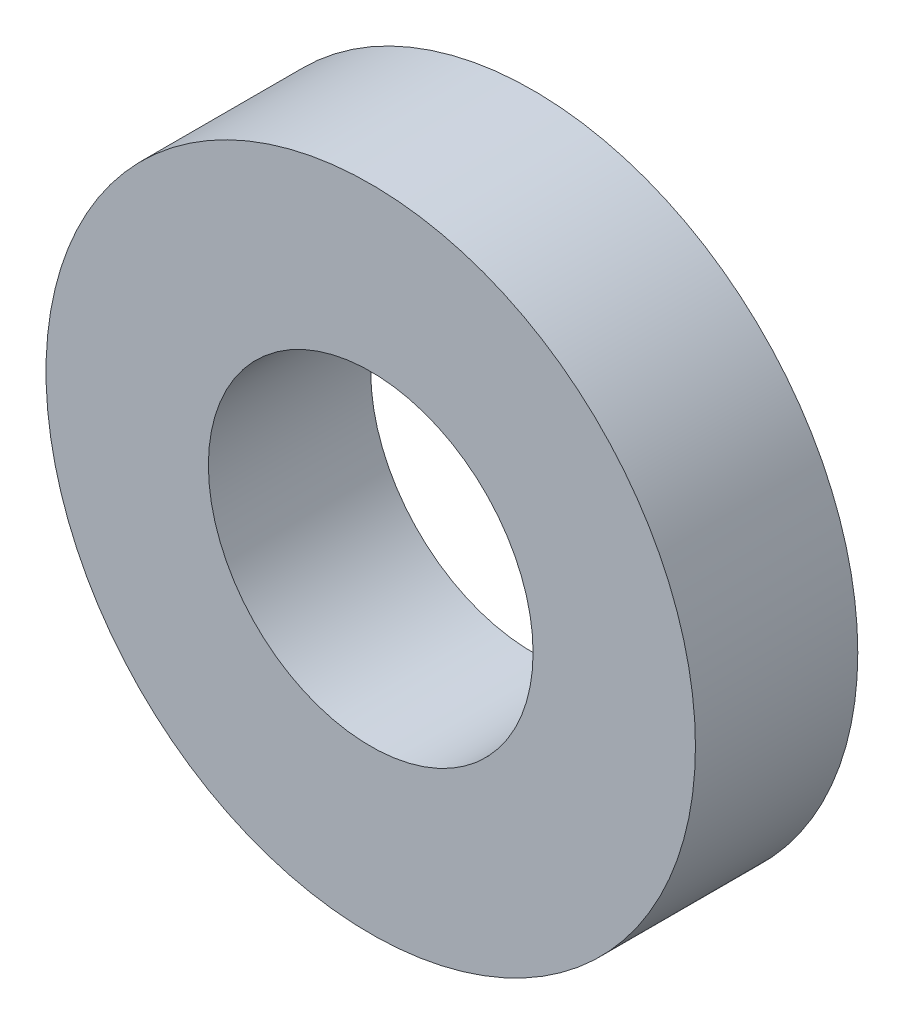
SolidWorks part; units mm, degrees
material "Acrylic (Medium-high impact)"
ref_plane "Front Plane" through (0, 0, 0) normal (0, 0, 1) x (1, 0, 0)
ref_plane "Top Plane" through (0, 0, 0) normal (0, 1, 0) x (1, 0, 0)
ref_plane "Right Plane" through (0, 0, 0) normal (1, 0, 0) x (0, 0, -1)
sketch "Sketch1" plane through (0, 0, 0) normal (0, 0, 1) x (1, 0, 0)
  circle A0 centre (0, 0) radius 5.08
  circle A1 centre (0, 0) radius 2.54
  dimension "D1" = 2.54
  dimension "D2" = 5.08
extrude "Boss-Extrude1" add sketch "Sketch1" along normal blind 2.54
